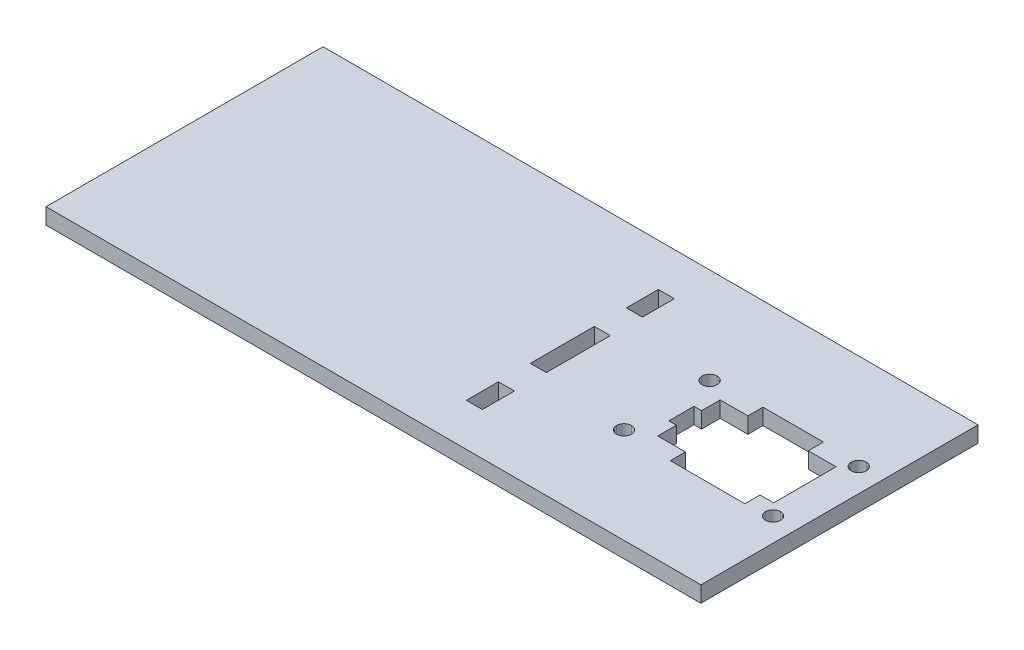
SolidWorks part; units mm, degrees
ref_plane "Front Plane" through (0, 0, 0) normal (0, 0, 1) x (1, 0, 0)
ref_plane "Top Plane" through (0, 0, 0) normal (0, 1, 0) x (1, 0, 0)
ref_plane "Right Plane" through (0, 0, 0) normal (1, 0, 0) x (0, 0, -1)
sketch "Sketch1" plane through (0, 0, 0) normal (0, 1, 0) x (1, 0, 0)
  line L0 (78.175, 40.2) -> (78.175, 14.8) construction
  line L1 (0, 0) -> (130, 0)
  line L2 (0, 0) -> (0, 55)
  line L3 (0, 55) -> (130, 55)
  line L4 (130, 0) -> (130, 55)
  line L5 (130, 27.5) -> (116.4302, 27.5) construction
  line L6 (75, 46.55) -> (78.175, 46.55)
  line L7 (75, 46.55) -> (75, 40.2)
  line L8 (75, 40.2) -> (78.175, 40.2)
  line L9 (78.175, 46.55) -> (78.175, 40.2)
  line L10 (75, 14.8) -> (78.175, 14.8)
  line L11 (75, 14.8) -> (75, 8.45)
  line L12 (75, 8.45) -> (78.175, 8.45)
  line L13 (78.175, 14.8) -> (78.175, 8.45)
  line L14 (78.175, 27.5) -> (47.2685, 27.5) construction
  line L15 (0, 27.5) -> (7.7524, 27.5) construction
  line L17 (78.175, 33.85) -> (75, 33.85)
  line L18 (78.175, 33.85) -> (78.175, 21.15)
  line L19 (78.175, 21.15) -> (75, 21.15)
  line L20 (75, 33.85) -> (75, 21.15)
  line B0 (123.1223, 27.5) -> (98.6224, 27.5) construction
  line B1 (98.6224, 25) -> (100.1223, 25)
  line B2 (100.1223, 25) -> (100.1223, 21.3)
  line B3 (100.1223, 21.3) -> (105.6223, 21.3)
  line B4 (105.6223, 21.3) -> (105.6223, 18.3002)
  line B5 (105.6223, 18.3002) -> (120.4223, 18.3002)
  line B6 (120.4223, 18.3002) -> (120.4223, 21.3)
  line B7 (120.4223, 21.3) -> (123.1223, 21.3)
  line B8 (123.1223, 21.3) -> (123.1223, 33.7)
  line B9 (123.1223, 33.7) -> (117.6223, 33.7)
  line B10 (117.6223, 33.7) -> (117.6223, 36.7)
  line B11 (117.6223, 36.7) -> (105.6223, 36.7)
  line B12 (105.6223, 36.7) -> (105.6223, 33.7)
  line B13 (105.6223, 33.7) -> (100.1223, 33.7)
  line B14 (100.1223, 33.7) -> (100.1223, 30)
  line B15 (100.1223, 30) -> (98.6224, 30)
  line B16 (98.6224, 30) -> (98.6224, 25)
  spline B17 degree 3 poles (97.2223, 36) (97.2223, 35.1715) (96.5508, 34.5) (95.7224, 34.5) knots 0 0 0 0 0.2 0.2 0.2 0.2
  spline B18 degree 3 poles (95.7224, 34.5) (94.8939, 34.4999) (94.2224, 35.1715) (94.2224, 35.9999) knots 0.2 0.2 0.2 0.2 0.4 0.4 0.4 0.4
  spline B19 degree 3 poles (94.2224, 35.9999) (94.2223, 36.8284) (94.8939, 37.4999) (95.7223, 37.5) knots 0.4 0.4 0.4 0.4 0.6 0.6 0.6 0.6
  spline B20 degree 3 poles (95.7223, 37.5) (96.5508, 37.5) (97.2223, 36.8284) (97.2223, 36) knots 0.6 0.6 0.6 0.6 1 1 1 1
  spline B21 degree 3 poles (126.8223, 19.0002) (126.8223, 18.1718) (126.1507, 17.5002) (125.3224, 17.5002) knots 0 0 0 0 0.2 0.2 0.2 0.2
  spline B22 degree 3 poles (125.3224, 17.5002) (124.494, 17.5002) (123.8224, 18.1718) (123.8224, 19.0001) knots 0.2 0.2 0.2 0.2 0.4 0.4 0.4 0.4
  spline B23 degree 3 poles (123.8224, 19.0001) (123.8224, 19.8285) (124.494, 20.4999) (125.3223, 20.4999) knots 0.4 0.4 0.4 0.4 0.6 0.6 0.6 0.6
  spline B24 degree 3 poles (125.3223, 20.4999) (126.1507, 20.4999) (126.8223, 19.8285) (126.8223, 19.0002) knots 0.6 0.6 0.6 0.6 1 1 1 1
  spline B25 degree 3 poles (97.2223, 19.0002) (97.2223, 18.1718) (96.5507, 17.5001) (95.7224, 17.5001) knots 0 0 0 0 0.2 0.2 0.2 0.2
  spline B26 degree 3 poles (95.7224, 17.5001) (94.894, 17.5001) (94.2223, 18.1718) (94.2223, 19.0001) knots 0.2 0.2 0.2 0.2 0.4 0.4 0.4 0.4
  spline B27 degree 3 poles (94.2223, 19.0001) (94.2223, 19.8285) (94.894, 20.5) (95.7223, 20.5) knots 0.4 0.4 0.4 0.4 0.6 0.6 0.6 0.6
  spline B28 degree 3 poles (95.7223, 20.5) (96.5507, 20.5) (97.2223, 19.8285) (97.2223, 19.0002) knots 0.6 0.6 0.6 0.6 1 1 1 1
  spline B29 degree 3 poles (126.8223, 36) (126.8223, 35.1715) (126.1508, 34.5001) (125.3224, 34.5001) knots 0 0 0 0 0.2 0.2 0.2 0.2
  spline B30 degree 3 poles (125.3224, 34.5001) (124.4939, 34.5) (123.8225, 35.1715) (123.8225, 35.9999) knots 0.2 0.2 0.2 0.2 0.4 0.4 0.4 0.4
  spline B31 degree 3 poles (123.8225, 35.9999) (123.8224, 36.8284) (124.4939, 37.4998) (125.3223, 37.4999) knots 0.4 0.4 0.4 0.4 0.6 0.6 0.6 0.6
  spline B32 degree 3 poles (125.3223, 37.4999) (126.1508, 37.4999) (126.8223, 36.8284) (126.8223, 36) knots 0.6 0.6 0.6 0.6 1 1 1 1
  dimension "D1" = 130
  dimension "D2" = 0
  dimension "D3" = 55
  dimension "D4" = 3.175
  dimension "D5" = 3.175
  dimension "D6" = 6.35
  dimension "D7" = 6.35
  dimension "D8" = 38.1
  dimension "D9" = 0
  dimension "D10" = 75
  dimension "D11" = 6.35
  dimension "D12" = 6.35
sketch_block_instance "Block1-1"
sketch_block "Block1"
extrude "Boss-Extrude1" add sketch "Sketch1" along normal blind 3.175
